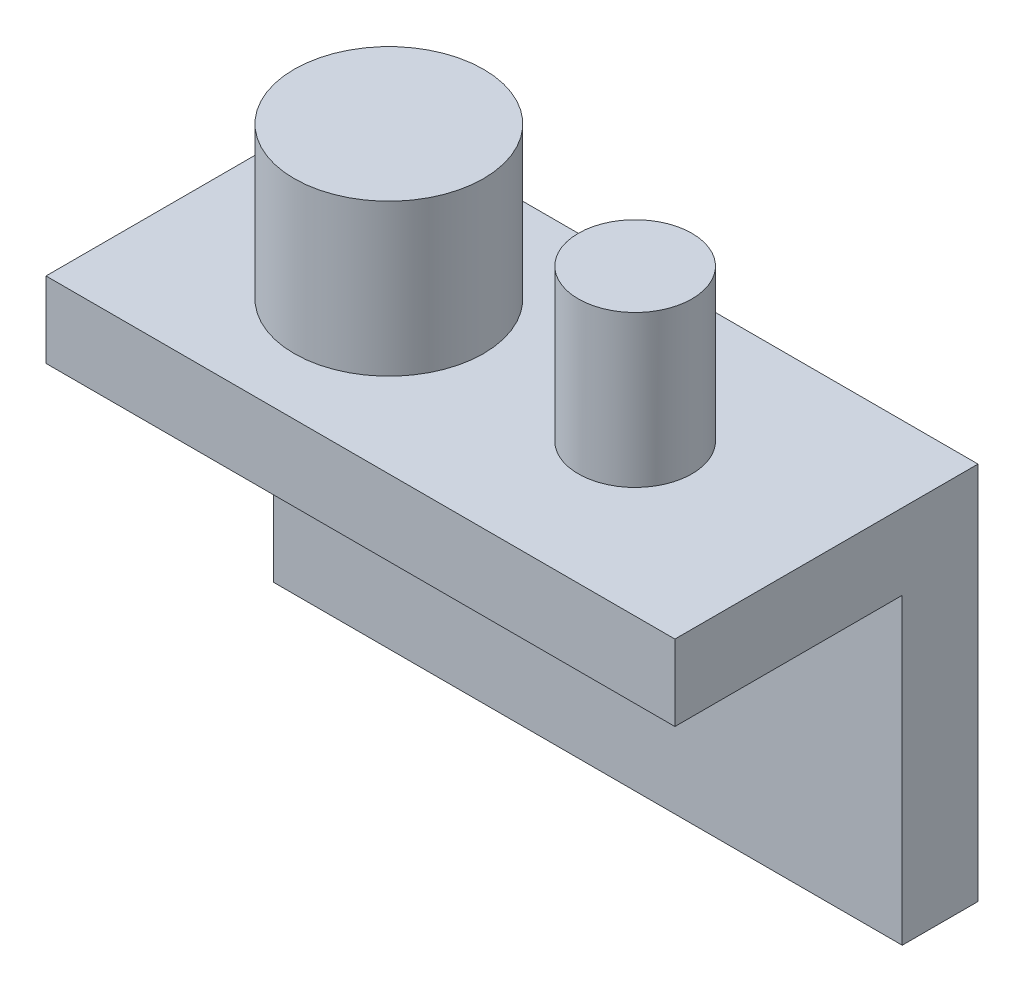
SolidWorks part; units mm, degrees
ref_plane "Front Plane" through (0, 0, 0) normal (0, 0, 1) x (1, 0, 0)
ref_plane "Top Plane" through (0, 0, 0) normal (0, 1, 0) x (1, 0, 0)
ref_plane "Right Plane" through (0, 0, 0) normal (1, 0, 0) x (0, 0, -1)
sketch "Sketch1" plane through (0, 0, 0) normal (0, 1, 0) x (1, 0, 0)
  line L0 (-11.6487, 0) -> (11.6487, 0) construction
  line L1 (-8.3, -4) -> (8.3, -4)
  line L2 (-8.3, -4) -> (-8.3, 4)
  line L3 (-8.3, 4) -> (8.3, 4)
  line L4 (8.3, -4) -> (8.3, 4)
  line L5 (-8.3, -4) -> (8.3, 4) construction
  line L6 (-8.3, 4) -> (8.3, -4) construction
  dimension "D1" = 16.6
  dimension "D2" = 8
extrude "Boss-Extrude1" add sketch "Sketch1" along normal blind 2
sketch "Sketch2" plane through (0, 2, 0) normal (0, 1, 0) x (1, 0, 0)
  line L0 (-11.0194, 0) -> (11.0194, 0) construction
  circle A0 centre (-3.25, 0) radius 2.5
  circle A1 centre (3.25, 0) radius 1.5
  point P4 (0, 0)
  dimension "D3" = 5
  dimension "D4" = 3
  dimension "D1" = 3.25
  dimension "D2" = 3.25
extrude "Boss-Extrude2" add sketch "Sketch2" along normal blind 4
sketch "Sketch3" plane through (0, 0, 0) normal (0, -1, 0) x (1, 0, 0)
  line L0 (8.3, 4) -> (8.3, -4) construction
  line L1 (-8.3, -4) -> (8.3, -4)
  line L2 (-8.3, -4) -> (-8.3, -2)
  line L3 (-8.3, -2) -> (8.3, -2)
  line L4 (8.3, -4) -> (8.3, -2)
  dimension "D1" = 2
extrude "Boss-Extrude3" add sketch "Sketch3" along normal blind 8
